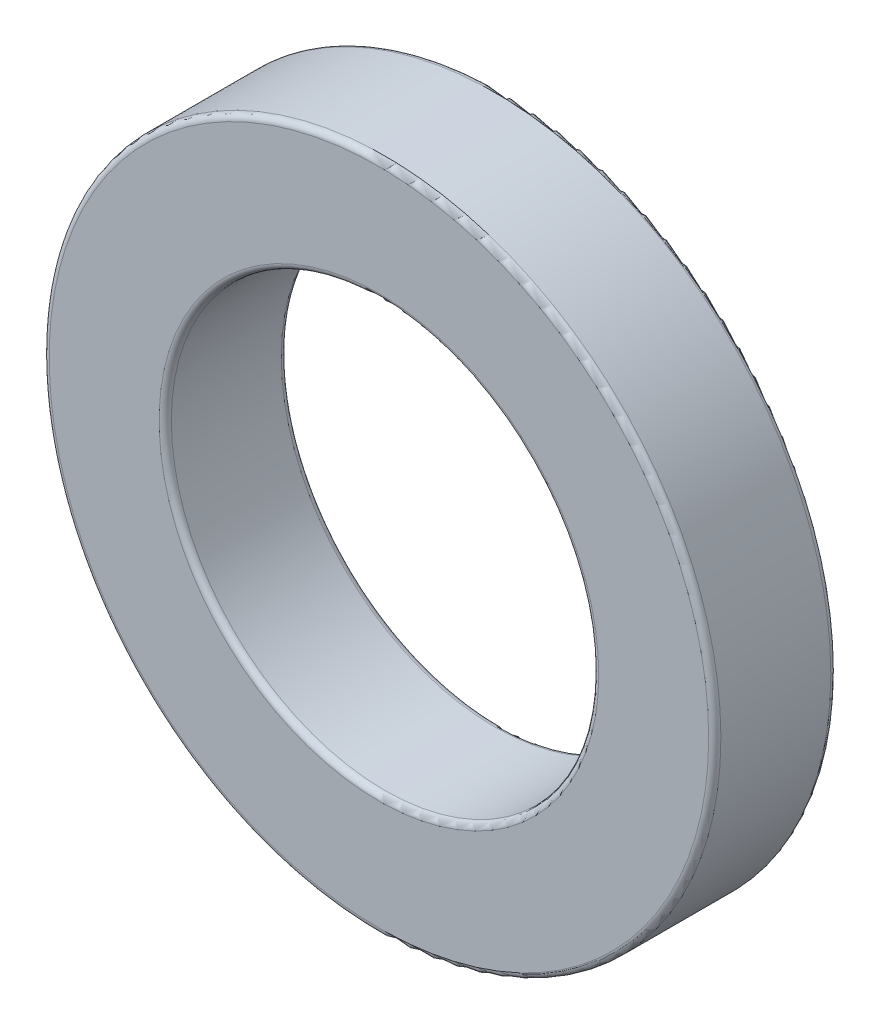
SolidWorks part; units mm, degrees
ref_plane "前视基准面" through (0, 0, 0) normal (0, 0, 1) x (1, 0, 0)
ref_plane "上视基准面" through (0, 0, 0) normal (0, 1, 0) x (1, 0, 0)
ref_plane "右视基准面" through (0, 0, 0) normal (1, 0, 0) x (0, 0, -1)
sketch "草图1" plane through (0, 0, 0) normal (0, 0, 1) x (1, 0, 0)
  circle A0 centre (0, 0) radius 27.5
  circle A1 centre (0, 0) radius 17.5
extrude "拉伸1" add sketch "草图1" along normal blind 10
fillet "圆角1" radius 0.5 4 edges at (27.5, 0, 0) (27.5, 0, 10) (17.5, 0, 0) (17.5, 0, 10)
